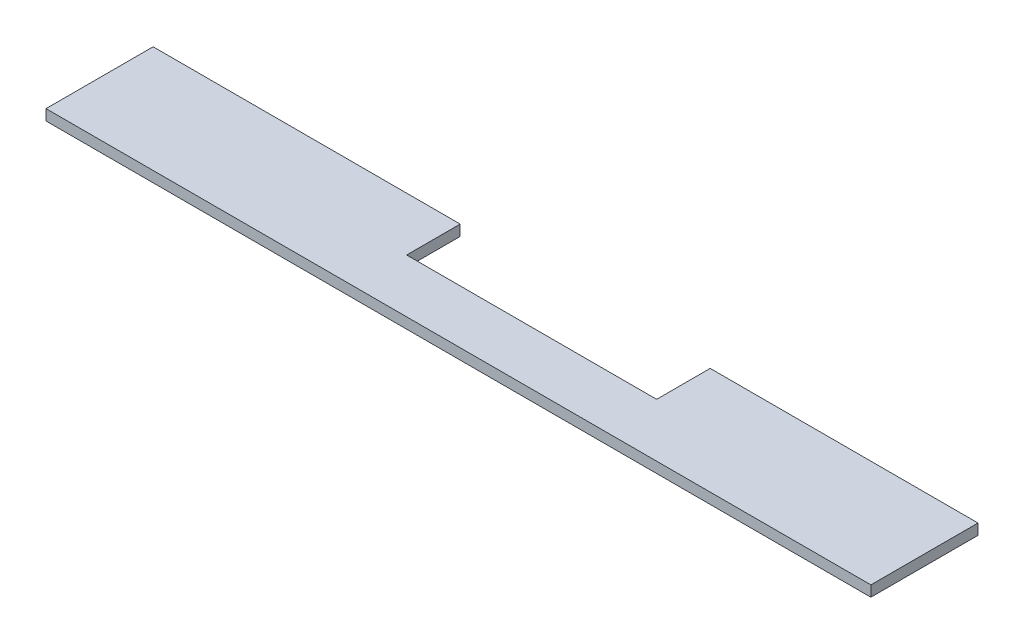
SolidWorks part; units mm, degrees
ref_plane "前基準面" through (0, 0, 0) normal (0, 0, 1) x (1, 0, 0)
ref_plane "上基準面" through (0, 0, 0) normal (0, 1, 0) x (1, 0, 0)
ref_plane "右基準面" through (0, 0, 0) normal (1, 0, 0) x (0, 0, -1)
sketch "草圖1" plane through (0, 0, 0) normal (0, 1, 0) x (1, 0, 0)
  line L0 (0, 0) -> (231, 0)
  line L1 (231, 0) -> (231, 30)
  line L2 (231, 30) -> (0, 30)
  line L3 (0, 30) -> (0, 0)
  dimension "D1" = 231
  dimension "D2" = 30
extrude "填料-伸長1" add sketch "草圖1" along normal blind 3
sketch "草圖2" plane through (0, 3, 0) normal (0, 1, 0) x (1, 0, 0)
  line L0 (231, 30) -> (0, 30) construction
  line L1 (86, 30) -> (156, 30)
  line L2 (86, 30) -> (86, 15)
  line L3 (86, 15) -> (156, 15)
  line L4 (156, 30) -> (156, 15)
  line L5 (231, 0) -> (231, 30) construction
  dimension "D1" = 15
  dimension "D2" = 70
  dimension "D3" = 75
extrude "除料-伸長1" cut sketch "草圖2" against normal through all
